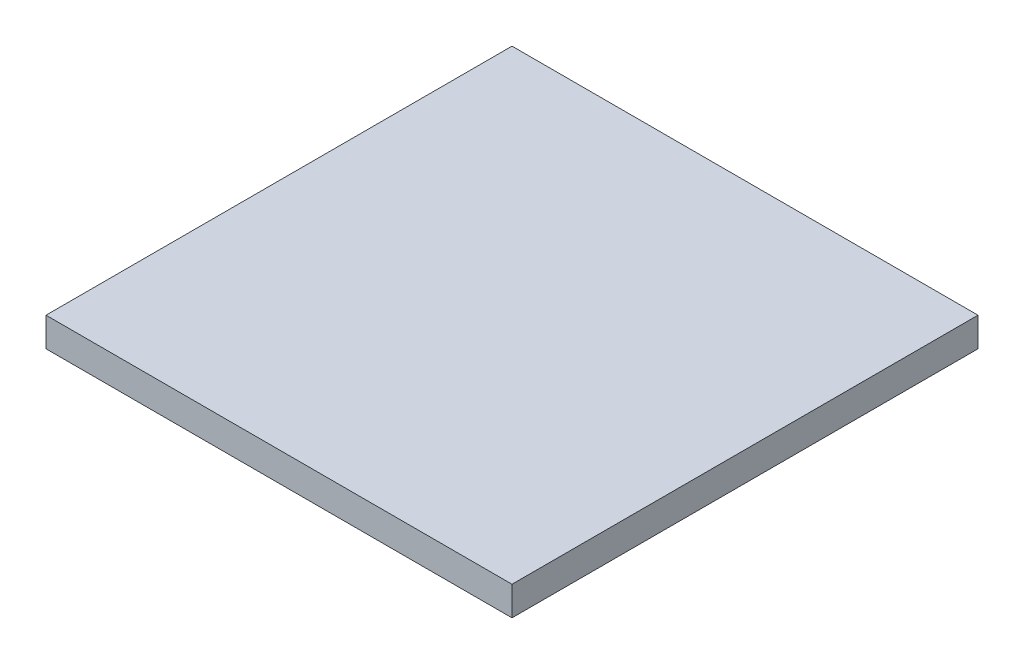
SolidWorks part; units mm, degrees
ref_plane "Front Plane" through (0, 0, 0) normal (0, 0, 1) x (1, 0, 0)
ref_plane "Top Plane" through (0, 0, 0) normal (0, 1, 0) x (1, 0, 0)
ref_plane "Right Plane" through (0, 0, 0) normal (1, 0, 0) x (0, 0, -1)
sketch "Sketch1" plane through (0, 0, 0) normal (0, 1, 0) x (1, 0, 0)
  line L1 (0, 0) -> (160, 0)
  line L2 (0, 0) -> (0, -160)
  line L3 (0, -160) -> (160, -160)
  line L4 (160, 0) -> (160, -160)
  dimension "D1" = 160
  dimension "D2" = 160
extrude "Boss-Extrude1" add sketch "Sketch1" along normal blind 10
